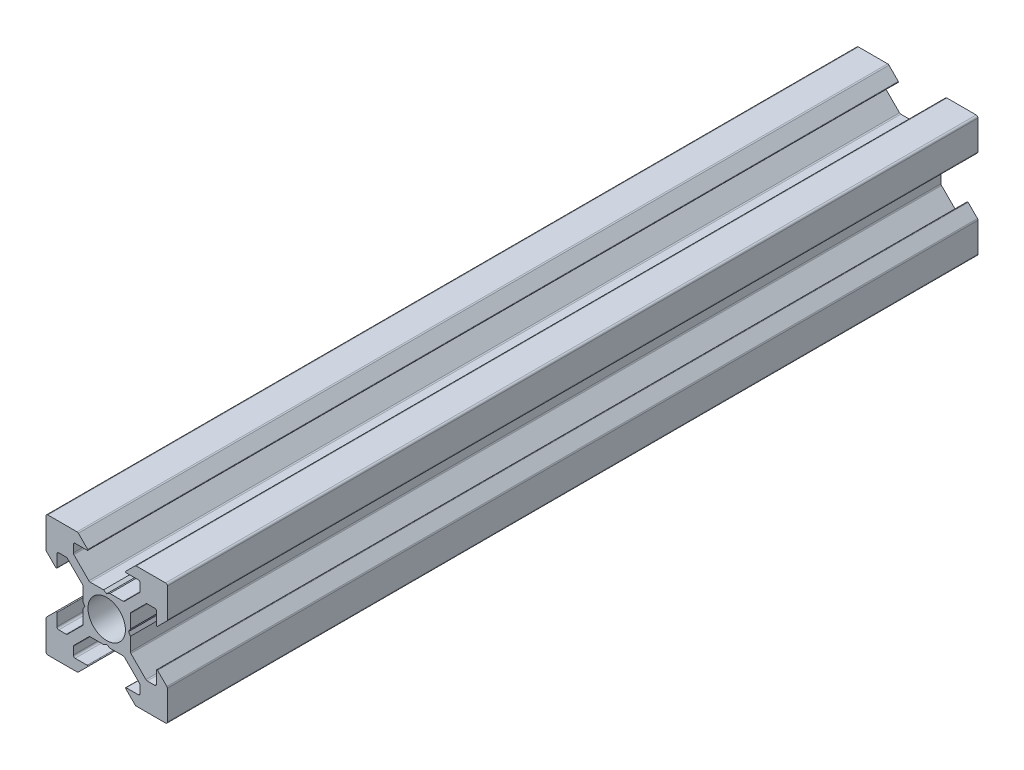
SolidWorks part; units mm, degrees
material "6063-T5"
ref_plane "Plan de face" through (0, 0, 0) normal (0, 0, 1) x (1, 0, 0)
ref_plane "Plan de dessus" through (0, 0, 0) normal (0, 1, 0) x (1, 0, 0)
ref_plane "Plan de droite" through (0, 0, 0) normal (1, 0, 0) x (0, 0, -1)
sketch "Esquisse1" plane through (0, 0, 0) normal (0, 0, 1) x (1, 0, 0)
  line L0 (18.274, -2.818) -> (18.274, -4.764)
  line L1 (17.982, -5.056) -> (16.7987, -5.056)
  line L2 (16.5922, -4.9705) -> (14.1749, -2.5531)
  line L3 (14.0893, -2.3466) -> (14.0893, -0.2091)
  line L4 (14.0893, -0.2091) -> (13.7973, 0.2966)
  line L5 (13.7973, 0.2966) -> (14.0893, 0.8024)
  line L6 (14.0893, 0.8024) -> (14.0893, 2.9399)
  line L7 (14.1749, 3.1464) -> (16.5922, 5.5637)
  line L8 (16.7987, 5.6493) -> (17.982, 5.6493)
  line L9 (18.274, 5.3573) -> (18.274, 3.4113)
  line L10 (18.4401, 3.3424) -> (19.9404, 4.8427)
  line L11 (20.026, 5.0492) -> (20.026, 9.7379)
  line L12 (19.734, 10.0299) -> (15.0453, 10.0299)
  line L13 (14.8388, 9.9443) -> (13.3385, 8.444)
  line L14 (13.4074, 8.2779) -> (15.3534, 8.2779)
  line L15 (15.6454, 7.9859) -> (15.6454, 6.8026)
  line L16 (15.5598, 6.5961) -> (13.1425, 4.1788)
  line L17 (12.936, 4.0932) -> (10.7985, 4.0932)
  line L18 (10.7985, 4.0932) -> (10.2927, 3.8012)
  line L19 (10.2927, 3.8012) -> (9.787, 4.0932)
  line L20 (9.787, 4.0932) -> (7.6495, 4.0932)
  line L21 (7.443, 4.1788) -> (5.0256, 6.5961)
  line L22 (4.9401, 6.8026) -> (4.9401, 7.9859)
  line L23 (5.2321, 8.2779) -> (7.1781, 8.2779)
  line L24 (7.2469, 8.444) -> (5.7466, 9.9443)
  line L25 (5.5402, 10.0299) -> (0.8515, 10.0299)
  line L26 (0.5595, 9.7379) -> (0.5595, 5.0492)
  line L27 (0.645, 4.8427) -> (2.1453, 3.3424)
  line L28 (2.3115, 3.4113) -> (2.3115, 5.3573)
  line L29 (2.6035, 5.6493) -> (3.7868, 5.6493)
  line L30 (3.9933, 5.5637) -> (6.4106, 3.1464)
  line L31 (6.4961, 2.9399) -> (6.4961, 0.8024)
  line L32 (6.4961, 0.8024) -> (6.7881, 0.2966)
  line L33 (6.7881, 0.2966) -> (6.4961, -0.2091)
  line L34 (6.4961, -0.2091) -> (6.4961, -2.3466)
  line L35 (6.4106, -2.5531) -> (3.9933, -4.9705)
  line L36 (3.7868, -5.056) -> (2.6035, -5.056)
  line L37 (2.3115, -4.764) -> (2.3115, -2.818)
  line L38 (2.1453, -2.7492) -> (0.645, -4.2495)
  line L39 (0.5595, -4.4559) -> (0.5595, -9.1446)
  line L40 (0.8515, -9.4366) -> (5.5402, -9.4366)
  line L41 (5.7466, -9.3511) -> (7.2469, -7.8508)
  line L42 (7.1781, -7.6846) -> (5.2321, -7.6846)
  line L43 (4.9401, -7.3926) -> (4.9401, -6.2093)
  line L44 (5.0256, -6.0028) -> (7.443, -3.5855)
  line L45 (7.6495, -3.5) -> (9.787, -3.5)
  line L46 (9.787, -3.5) -> (10.2927, -3.208)
  line L47 (10.2927, -3.208) -> (10.7985, -3.5)
  line L48 (10.7985, -3.5) -> (12.936, -3.5)
  line L49 (13.1425, -3.5855) -> (15.5598, -6.0028)
  line L50 (15.6454, -6.2093) -> (15.6454, -7.3926)
  line L51 (15.3534, -7.6846) -> (13.4074, -7.6846)
  line L52 (13.3385, -7.8508) -> (14.8388, -9.3511)
  line L53 (15.0453, -9.4366) -> (19.734, -9.4366)
  line L54 (20.026, -9.1446) -> (20.026, -4.4559)
  line L55 (19.9404, -4.2495) -> (18.4401, -2.7492)
  arc A4 (18.4401, -2.7492) -> (18.274, -2.818) centre (18.3713, -2.818) ccw
  arc A5 (17.982, -5.056) -> (18.274, -4.764) centre (17.982, -4.764) ccw
  arc A6 (16.5922, -4.9705) -> (16.7987, -5.056) centre (16.7987, -4.764) ccw
  arc A7 (14.0893, -2.3466) -> (14.1749, -2.5531) centre (14.3813, -2.3466) ccw
  arc A8 (14.1749, 3.1464) -> (14.0893, 2.9399) centre (14.3813, 2.9399) ccw
  arc A9 (16.7987, 5.6493) -> (16.5922, 5.5637) centre (16.7987, 5.3573) ccw
  arc A10 (18.274, 5.3573) -> (17.982, 5.6493) centre (17.982, 5.3573) ccw
  arc A11 (18.274, 3.4113) -> (18.4401, 3.3424) centre (18.3713, 3.4113) ccw
  arc A12 (19.9404, 4.8427) -> (20.026, 5.0492) centre (19.734, 5.0492) ccw
  arc A13 (20.026, 9.7379) -> (19.734, 10.0299) centre (19.734, 9.7379) ccw
  arc A14 (15.0453, 10.0299) -> (14.8388, 9.9443) centre (15.0453, 9.7379) ccw
  arc A15 (13.3385, 8.444) -> (13.4074, 8.2779) centre (13.4074, 8.3752) ccw
  arc A16 (15.6454, 7.9859) -> (15.3534, 8.2779) centre (15.3534, 7.9859) ccw
  arc A17 (15.5598, 6.5961) -> (15.6454, 6.8026) centre (15.3534, 6.8026) ccw
  arc A18 (12.936, 4.0932) -> (13.1425, 4.1788) centre (12.936, 4.3852) ccw
  arc A19 (7.443, 4.1788) -> (7.6495, 4.0932) centre (7.6495, 4.3852) ccw
  arc A20 (4.9401, 6.8026) -> (5.0256, 6.5961) centre (5.2321, 6.8026) ccw
  arc A21 (5.2321, 8.2779) -> (4.9401, 7.9859) centre (5.2321, 7.9859) ccw
  arc A22 (7.1781, 8.2779) -> (7.2469, 8.444) centre (7.1781, 8.3752) ccw
  arc A23 (5.7466, 9.9443) -> (5.5402, 10.0299) centre (5.5402, 9.7379) ccw
  arc A24 (0.8515, 10.0299) -> (0.5595, 9.7379) centre (0.8515, 9.7379) ccw
  arc A25 (0.5595, 5.0492) -> (0.645, 4.8427) centre (0.8515, 5.0492) ccw
  arc A26 (2.1453, 3.3424) -> (2.3115, 3.4113) centre (2.2142, 3.4113) ccw
  arc A27 (2.6035, 5.6493) -> (2.3115, 5.3573) centre (2.6035, 5.3573) ccw
  arc A28 (3.9933, 5.5637) -> (3.7868, 5.6493) centre (3.7868, 5.3573) ccw
  arc A29 (6.4961, 2.9399) -> (6.4106, 3.1464) centre (6.2041, 2.9399) ccw
  arc A30 (6.4106, -2.5531) -> (6.4961, -2.3466) centre (6.2041, -2.3466) ccw
  arc A31 (3.7868, -5.056) -> (3.9933, -4.9705) centre (3.7868, -4.764) ccw
  arc A32 (2.3115, -4.764) -> (2.6035, -5.056) centre (2.6035, -4.764) ccw
  arc A33 (2.3115, -2.818) -> (2.1453, -2.7492) centre (2.2142, -2.818) ccw
  arc A34 (0.645, -4.2495) -> (0.5595, -4.4559) centre (0.8515, -4.4559) ccw
  arc A35 (0.5595, -9.1446) -> (0.8515, -9.4366) centre (0.8515, -9.1446) ccw
  arc A36 (5.5402, -9.4366) -> (5.7466, -9.3511) centre (5.5402, -9.1446) ccw
  arc A37 (7.2469, -7.8508) -> (7.1781, -7.6846) centre (7.1781, -7.7819) ccw
  arc A38 (4.9401, -7.3926) -> (5.2321, -7.6846) centre (5.2321, -7.3926) ccw
  arc A39 (5.0256, -6.0028) -> (4.9401, -6.2093) centre (5.2321, -6.2093) ccw
  arc A40 (7.6495, -3.5) -> (7.443, -3.5855) centre (7.6495, -3.792) ccw
  arc A41 (13.1425, -3.5855) -> (12.936, -3.5) centre (12.936, -3.792) ccw
  arc A42 (15.6454, -6.2093) -> (15.5598, -6.0028) centre (15.3534, -6.2093) ccw
  arc A43 (15.3534, -7.6846) -> (15.6454, -7.3926) centre (15.3534, -7.3926) ccw
  arc A44 (13.4074, -7.6846) -> (13.3385, -7.8508) centre (13.4074, -7.7819) ccw
  arc A45 (14.8388, -9.3511) -> (15.0453, -9.4366) centre (15.0453, -9.1446) ccw
  arc A46 (19.734, -9.4366) -> (20.026, -9.1446) centre (19.734, -9.1446) ccw
  arc A47 (20.026, -4.4559) -> (19.9404, -4.2495) centre (19.734, -4.4559) ccw
  circle A48 centre (10.2927, 0.2966) radius 3
  dimension "D1" = 6
extrude "Boss.-Extru.1" add sketch "Esquisse1" along normal blind 130
